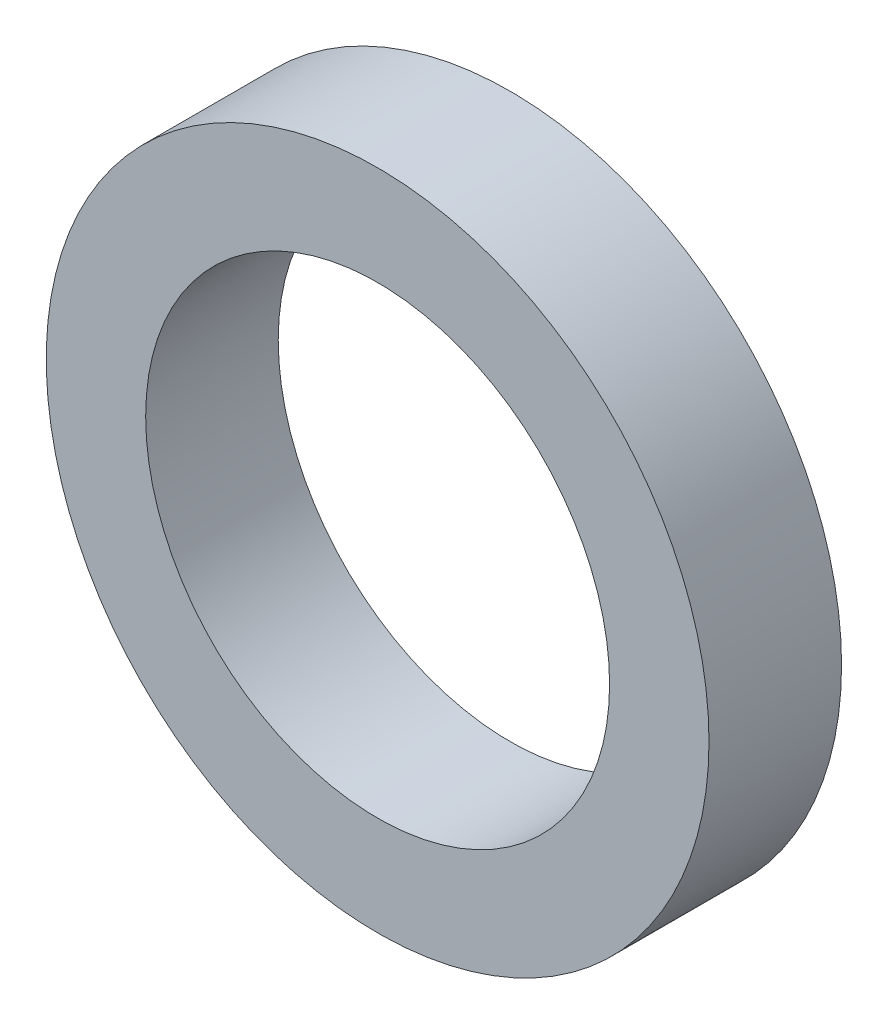
SolidWorks part; units mm, degrees
ref_plane "Front Plane" through (0, 0, 0) normal (0, 0, 1) x (1, 0, 0)
ref_plane "Top Plane" through (0, 0, 0) normal (0, 1, 0) x (1, 0, 0)
ref_plane "Right Plane" through (0, 0, 0) normal (1, 0, 0) x (0, 0, -1)
sketch "Sketch1" plane through (0, 0, 0) normal (0, 0, 1) x (1, 0, 0)
  circle A0 centre (0, 0) radius 3.5
  circle A1 centre (0, 0) radius 5
  dimension "D1" = 10
  dimension "D2" = 7
extrude "Boss-Extrude1" add sketch "Sketch1" along normal blind 2
